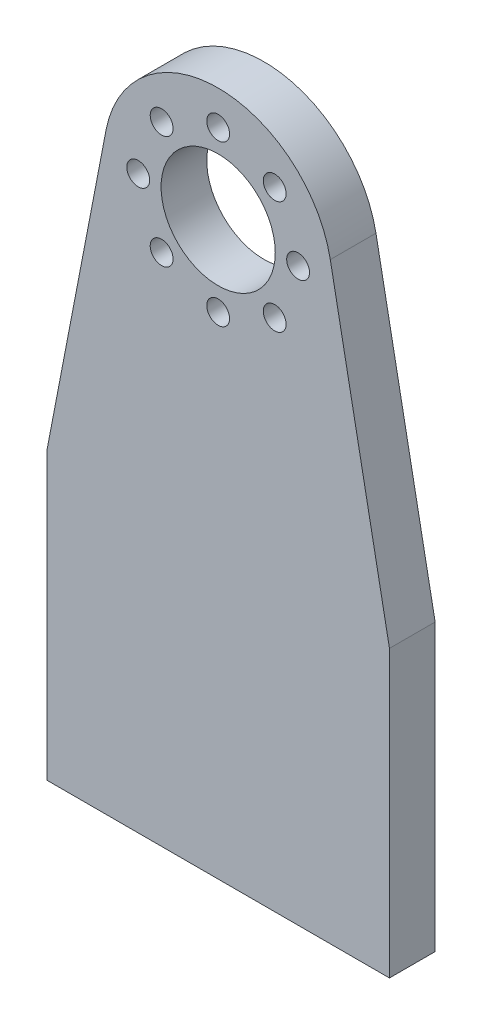
SolidWorks part; units mm, degrees
ref_plane "Front Plane" through (0, 0, 0) normal (0, 0, 1) x (1, 0, 0)
ref_plane "Top Plane" through (0, 0, 0) normal (0, 1, 0) x (1, 0, 0)
ref_plane "Right Plane" through (0, 0, 0) normal (1, 0, 0) x (0, 0, -1)
sketch "Sketch1" plane through (0, 0, 0) normal (0, 0, 1) x (1, 0, 0)
  line L0 (-15, -7.8963) -> (-9.8194, 18.9953)
  line L2 (-15, -7.8963) -> (-15, -32.8963)
  line L3 (-15, -32.8963) -> (15, -32.8963)
  line L5 (-17.1046, 37.5119) -> (15, -32.8963) construction
  line L6 (-15, -32.8963) -> (16.601, 36.4074) construction
  line L7 (0, 17.1037) -> (0, 0) construction
  line L8 (15, -7.8963) -> (15, -32.8963)
  line L9 (15, -7.8963) -> (9.8194, 18.9953)
  arc A0 (-9.8194, 18.9953) -> (9.8194, 18.9953) centre (0, 17.1037) cw
  circle A1 centre (0, 24.1037) radius 1
  circle A2 centre (4.9497, 22.0534) radius 1
  circle A3 centre (7, 17.1037) radius 1
  circle A4 centre (4.9497, 12.1539) radius 1
  circle A5 centre (0, 10.1037) radius 1
  circle A6 centre (-4.9497, 12.1539) radius 1
  circle A7 centre (-7, 17.1037) radius 1
  circle A8 centre (-4.9497, 22.0534) radius 1
  circle A9 centre (0, 17.1037) radius 5
  point P1 (0, 0)
  dimension "D1" = 10
  dimension "D6" = 2
  dimension "D8" = 10
  dimension "D2" = 50
  dimension "D3" = 25
  dimension "D4" = 30
  dimension "D5" = 7
  dimension "D7" = 8
extrude "Boss-Extrude1" add sketch "Sketch1" along normal blind 4
